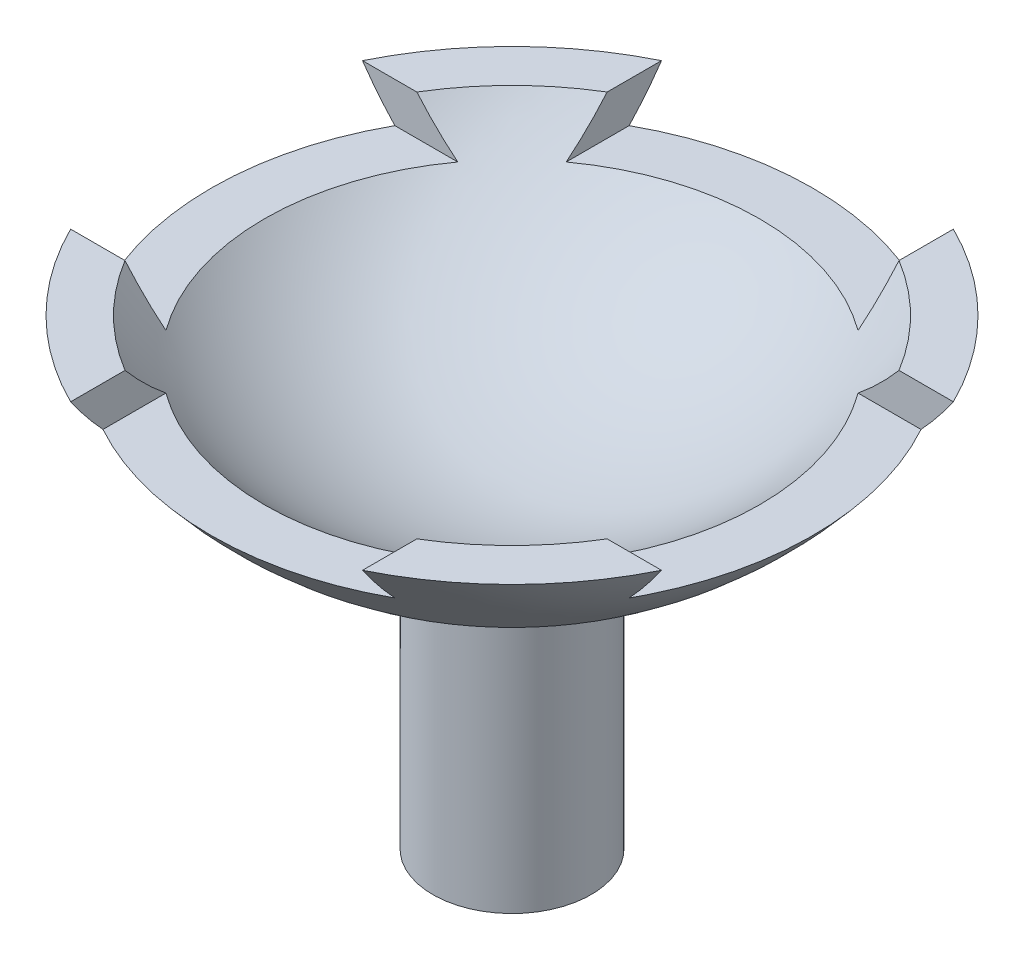
SolidWorks part; units mm, degrees
ref_plane "Front Plane" through (0, 0, 0) normal (0, 0, 1) x (1, 0, 0)
ref_plane "Top Plane" through (0, 0, 0) normal (0, 1, 0) x (1, 0, 0)
ref_plane "Right Plane" through (0, 0, 0) normal (1, 0, 0) x (0, 0, -1)
sketch "Sketch1" plane through (0, 0, 0) normal (0, 0, 1) x (1, 0, 0)
  line L0 (0, 24.1312) -> (0, 21.1312)
  line L2 (21.3481, 35) -> (24.9628, 35)
  line L3 (0, 0) -> (6, 0)
  line L4 (6, 0) -> (6, 21.75)
  line L5 (0, 21.1312) -> (0, 0)
  arc A0 (6, 21.75) -> (24.9628, 35) centre (0, 50.5312) ccw
  arc A1 (0, 24.1312) -> (21.3481, 35) centre (0, 50.5312) ccw
  arc A2 (0, 24.1312) -> (26.4, 50.5312) centre (0, 50.5312) ccw construction
  arc A3 (0, 21.1312) -> (29.4, 50.5312) centre (0, 50.5312) ccw construction
  dimension "D2" = 29.4
  dimension "D3" = 21.75
  dimension "D4" = 35
  dimension "D5" = 6
  dimension "D1" = 3
revolve "Revolve1" add sketch "Sketch1" angle 360 about L5
sketch "Sketch2" plane through (0, 0, 0) normal (0, 0, 1) x (1, 0, 0)
  line L0 (21.3481, 35) -> (-21.3481, 35) construction
  line L1 (-11.055, 35) -> (11.055, 35)
  line L2 (-11.055, 35) -> (-11.055, 31.96)
  line L3 (-11.055, 31.96) -> (11.055, 31.96)
  line L4 (11.055, 35) -> (11.055, 31.96)
  line L5 (0, 0) -> (0, 13.8569) construction
  dimension "D1" = 22.11
  dimension "D2" = 3.04
extrude "Cut-Extrude1" cut sketch "Sketch2" against normal up to next
pattern_circular "CirPattern1" count 4 over 360 about axis through (0, 0, 0) along (0, 1, 0) of "Cut-Extrude1"
fillet "Fillet1" radius 1.5 1 edges at (-6, 21.75, 0)
